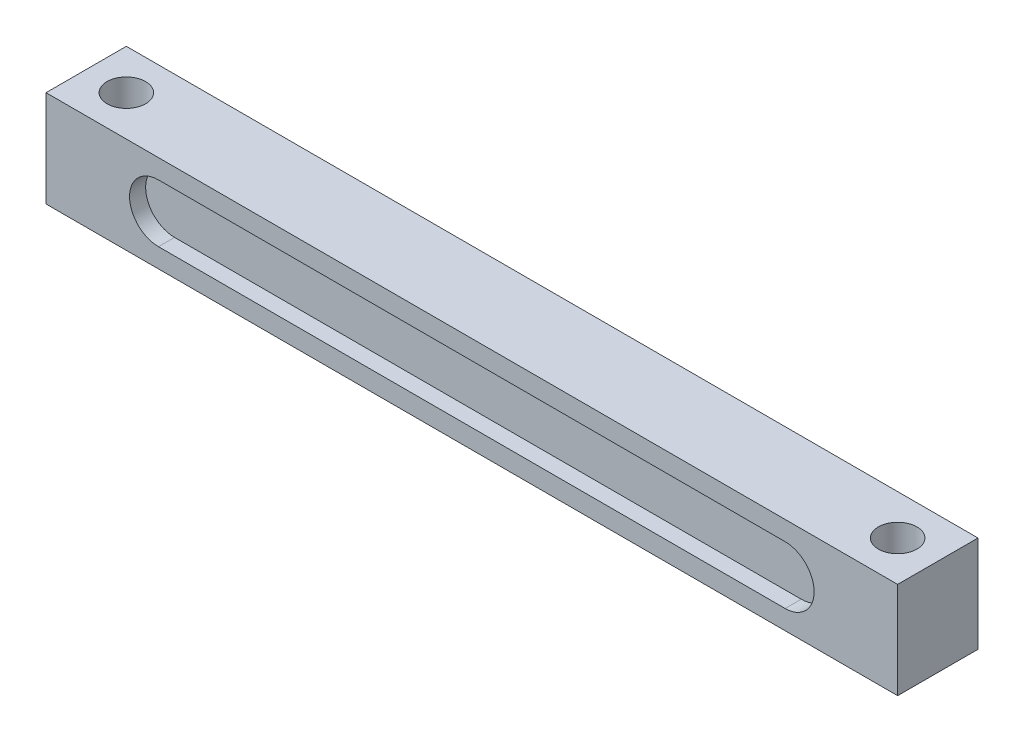
SolidWorks part; units mm, degrees
material "ASTM A36 Steel"
ref_plane "Front Plane" through (0, 0, 0) normal (0, 0, 1) x (1, 0, 0)
ref_plane "Top Plane" through (0, 0, 0) normal (0, 1, 0) x (1, 0, 0)
ref_plane "Right Plane" through (0, 0, 0) normal (1, 0, 0) x (0, 0, -1)
sketch "Sketch1" plane through (0, 0, 0) normal (0, 1, 0) x (1, 0, 0)
  line L1 (0, 0) -> (336.55, 0)
  line L2 (0, 0) -> (0, 31.75)
  line L3 (0, 31.75) -> (336.55, 31.75)
  line L4 (336.55, 0) -> (336.55, 31.75)
  circle A0 centre (15.875, 15.875) radius 7.62
  circle A1 centre (320.675, 15.875) radius 7.62
  dimension "D3" = 15.24
  dimension "D1" = 336.55
  dimension "D2" = 31.75
  dimension "D4" = 304.8
  dimension "D5" = 15.875
  dimension "D6" = 15.875
extrude "Boss-Extrude1" add sketch "Sketch1" along normal blind 38.1
sketch "Sketch2" plane through (0, 0, 0) normal (0, -1, 0) x (1, 0, 0)
  circle A0 centre (15.875, -15.875) radius 15.875
  circle A1 centre (320.675, -15.875) radius 15.875
  dimension "D1" = 31.75
sketch "Sketch3" plane through (0, 0, 0) normal (0, -1, 0) x (1, 0, 0)
  line L0 (336.55, -31.75) -> (0, -31.75) construction
  line L1 (152.4, -31.75) -> (184.15, -31.75)
  line L2 (152.4, -31.75) -> (152.4, 0)
  line L3 (152.4, 0) -> (184.15, 0)
  line L4 (184.15, -31.75) -> (184.15, 0)
  line L5 (0, 0) -> (336.55, 0) construction
  point P8 (168.275, -31.75)
  point P9 (168.275, -31.75)
split line "Split Line2"
split line "Split Line3"
sketch "Sketch4" plane through (0, 0, 0) normal (0, 0, 1) x (1, 0, 0)
  line L0 (44.45, 19.05) -> (292.1, 19.05) construction
  line L1 (44.45, 30.48) -> (292.1, 30.48)
  line L2 (44.45, 7.62) -> (292.1, 7.62)
  line L3 (0, 38.1) -> (0, 0) construction
  line L4 (0, 38.1) -> (336.55, 38.1) construction
  arc A0 (44.45, 30.48) -> (44.45, 7.62) centre (44.45, 19.05) ccw
  arc A1 (292.1, 7.62) -> (292.1, 30.48) centre (292.1, 19.05) ccw
  point P2 (168.275, 19.05)
  point P9 (0, 19.05)
  point P10 (0, 0)
  point P13 (168.275, 38.1)
  point P14 (47.9066, 19.05)
  dimension "D2" = 44.45
  dimension "D1" = 7.62
extrude "Cut-Extrude1" cut sketch "Sketch4" against normal blind 6.35
sketch "Sketch6" plane through (0, 0, -31.75) normal (0, 0, -1) x (-1, 0, 0)
  line L0 (-292.1, 19.05) -> (-44.45, 19.05) construction
  line L1 (-292.1, 30.48) -> (-44.45, 30.48)
  line L2 (-292.1, 7.62) -> (-44.45, 7.62)
  line L3 (-184.15, 0) -> (-152.4, 0) construction
  line L4 (-336.55, 38.1) -> (-336.55, 0) construction
  arc A0 (-292.1, 30.48) -> (-292.1, 7.62) centre (-292.1, 19.05) ccw
  arc A1 (-44.45, 7.62) -> (-44.45, 30.48) centre (-44.45, 19.05) ccw
  point P2 (-168.275, 19.05)
  point P11 (-336.55, 19.05)
  point P12 (0, 0)
  point P13 (-168.275, 0)
  dimension "D2" = 44.45
  dimension "D1" = 7.62
extrude "Cut-Extrude3" cut sketch "Sketch6" against normal blind 6.35
equation "\"L\"= 12"
equation "\"D\"= .6"
equation "\"W\"= 1.25"
equation "\"Lo\"= \"L\" + \"W\""
equation "\"Th\"= 1.11'solved previously in mm and converted"
equation "\"D1@Sketch1\"=\"Lo\""
equation "\"D2@Sketch1\"=\"W\""
equation "\"D3@Sketch1\"=\"D\""
equation "\"D4@Sketch1\"=\"L\""
equation "\"D1@Boss-Extrude1\"=\"Th\""
